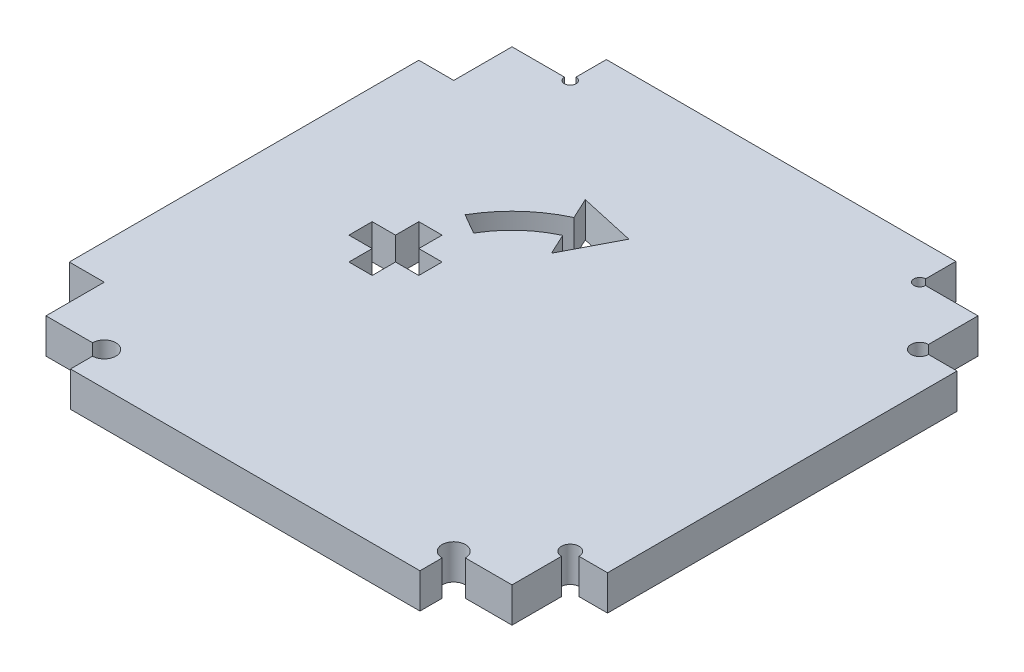
SolidWorks part; units mm, degrees
ref_plane "Front Plane" through (0, 0, 0) normal (0, 0, 1) x (1, 0, 0)
ref_plane "Top Plane" through (0, 0, 0) normal (0, 1, 0) x (1, 0, 0)
ref_plane "Right Plane" through (0, 0, 0) normal (1, 0, 0) x (0, 0, -1)
sketch "Sketch1" plane through (0, 0, 0) normal (0, 1, 0) x (1, 0, 0)
  line L0 (-20, -20) -> (-20, -15)
  line L1 (-20, 20) -> (20, 20) construction
  line L2 (-20, 20) -> (-20, -20) construction
  line L3 (-20, -20) -> (20, -20) construction
  line L4 (20, 20) -> (20, -20) construction
  line L5 (0, -20) -> (0, 20) construction
  line L6 (-20, 0) -> (20, 0) construction
  line L7 (-20, -15) -> (-23, -15)
  line L8 (-23, -15) -> (-23, 15)
  line L9 (-23, 15) -> (-20, 15)
  line L10 (-20, 15) -> (-20, 20)
  line L11 (-20, 20) -> (-15, 20)
  line L12 (-15, 20) -> (-15, 23.1)
  line L13 (-15, 23.1) -> (15, 23.1)
  line L14 (15, 23.1) -> (15, 20)
  line L15 (15, 20) -> (20, 20)
  line L16 (20, 20) -> (20, 15)
  line L17 (20, 15) -> (23.2, 15)
  line L18 (23.2, 15) -> (23.2, -15)
  line L19 (23.2, -15) -> (20, -15)
  line L20 (20, -15) -> (20, -20)
  line L21 (20, -20) -> (15, -20)
  line L22 (15, -20) -> (15, -22.9)
  line L23 (15, -22.9) -> (-15, -22.9)
  line L24 (-15, -22.9) -> (-15, -20)
  line L25 (-15, -20) -> (-20, -20)
  line L27 (-13, -1) -> (-11, -1)
  line L28 (-13, -1) -> (-13, 1)
  line L29 (-13, 1) -> (-11, 1)
  line L30 (-7, -1) -> (-7, 1)
  line L31 (-9.5263, 5.5) -> (-7.7942, 4.5)
  line L32 (-13, 0) -> (-7, 0) construction
  line L37 (-3.8036, 8.1568) -> (-2.9583, 6.3442)
  line L38 (-2.9583, 6.3442) -> (-0.6828, 10.7154)
  line L42 (-9, -1) -> (-7, -1)
  line L43 (-9, 3) -> (-11, 3)
  line L44 (-9, 3) -> (-9, 1)
  line L45 (-9, -3) -> (-11, -3)
  line L46 (-11, 3) -> (-11, 1)
  line L47 (-10, -3) -> (-10, 3) construction
  line L48 (-0.6828, 10.7154) -> (-5.494, 11.782)
  line L49 (-9, -1) -> (-9, -3)
  line L50 (-9, 1) -> (-7, 1)
  line L51 (-11, -1) -> (-11, -3)
  line L52 (-5.494, 11.782) -> (-4.6488, 9.9694)
  line L53 (-3.8036, 8.1568) -> (-4.6488, 9.9694) construction
  line L54 (-4.2262, 9.0631) -> (-0.6828, 10.7154) construction
  arc A0 (-7.7942, 4.5) -> (-3.8036, 8.1568) centre (0, 0) cw
  arc A1 (-9.5263, 5.5) -> (-4.6488, 9.9694) centre (0, 0) cw
  arc A2 (-10, 0) -> (-4.2262, 9.0631) centre (0, 0) cw construction
  point P20 (-10, 0)
  point P43 (-10, 0)
  point P84 (0, 0)
  dimension "D13" = 75
  dimension "D16" = 35
  dimension "D1" = 40
  dimension "D2" = 40
  dimension "D3" = 3
  dimension "D4" = 3.1
  dimension "D5" = 3.2
  dimension "D6" = 2.9
  dimension "D7" = 30
  dimension "D8" = 30
  dimension "D9" = 30
  dimension "D10" = 30
  dimension "D11" = 2
  dimension "D12" = 6
  dimension "D14" = 2
  dimension "D15" = 6
  dimension "D17" = 30
  dimension "D18" = 2
  dimension "D19" = 6
  dimension "D20" = 10
extrude "Boss-Extrude1" add sketch "Sketch1" along normal blind 3
sketch "Sketch4" plane through (0, 3, 0) normal (0, 1, 0) x (1, 0, 0)
  circle A2 centre (-15, 20) radius 0.5
  circle A3 centre (15, 20) radius 0.5
  circle A4 centre (20, 15) radius 0.75
  circle A5 centre (20, -15) radius 0.75
  circle A6 centre (15, -20) radius 1
  circle A7 centre (-15, -20) radius 1
  dimension "D3" = 1
  dimension "D4" = 1
  dimension "D5" = 2
  dimension "D6" = 2
  dimension "D7" = 1.5
  dimension "D8" = 1.5
extrude "Cut-Extrude1" cut sketch "Sketch4" against normal through all
